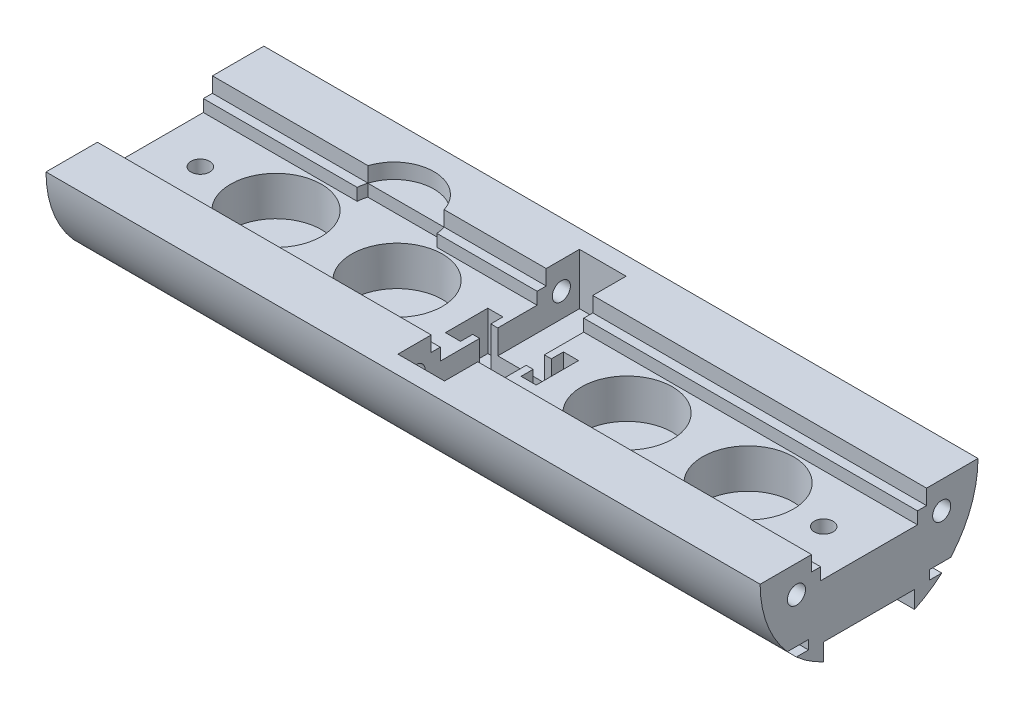
SolidWorks part; units mm, degrees
ref_plane "Front Plane" through (0, 0, 0) normal (0, 0, 1) x (1, 0, 0)
ref_plane "Top Plane" through (0, 0, 0) normal (0, 1, 0) x (1, 0, 0)
ref_plane "Right Plane" through (0, 0, 0) normal (1, 0, 0) x (0, 0, -1)
sketch "Sketch1" plane through (0, 0, 0) normal (1, 0, 0) x (0, 0, -1)
  line L0 (-49.53, 0) -> (-24.13, 0)
  line L1 (-24.13, 0) -> (-24.13, -6.35)
  line L2 (-24.13, -6.35) -> (-20.32, -6.35)
  line L3 (-20.32, -6.35) -> (-20.32, -11.43)
  line L4 (24.13, 0) -> (49.53, 0)
  line L5 (-20.32, -11.43) -> (20.32, -11.43)
  line L6 (20.32, -11.43) -> (20.32, -6.35)
  line L7 (20.32, -6.35) -> (24.13, -6.35)
  line L8 (24.13, -6.35) -> (24.13, 0)
  arc A0 (-49.53, 0) -> (49.53, 0) centre (0, 0) ccw
  dimension "D1" = 99.06
  dimension "D2" = 25.4
  dimension "D3" = 25.4
  dimension "D4" = 6.35
  dimension "D5" = 3.81
  dimension "D6" = 3.81
  dimension "D7" = 5.08
sketch "Sketch3" plane through (0, 0, 0) normal (1, 0, 0) x (0, 0, -1)
  line L0 (-49.53, 0) -> (-24.13, 0)
  line L1 (-24.13, 0) -> (-24.13, -6.35)
  line L2 (-24.13, -6.35) -> (-20.32, -6.35)
  line L3 (-20.32, -6.35) -> (-20.32, -11.43)
  line L4 (-20.32, -11.43) -> (20.32, -11.43)
  line L5 (20.32, -11.43) -> (20.32, -6.35)
  line L6 (20.32, -6.35) -> (24.13, -6.35)
  line L7 (24.13, -6.35) -> (24.13, 0)
  line L8 (24.13, 0) -> (49.53, 0)
  line L9 (0, 0) -> (0, -49.53) construction
  line L10 (19.05, -34.29) -> (-19.05, -34.29)
  line L11 (-19.05, -34.29) -> (-19.05, -45.72)
  line L12 (19.05, -34.29) -> (19.05, -45.72)
  arc A0 (-49.53, 0) -> (-19.05, -45.72) centre (0, 0) ccw
  arc A1 (-49.53, 0) -> (49.53, 0) centre (0, 0) ccw construction
  arc A2 (19.05, -45.72) -> (49.53, 0) centre (0, 0) ccw
  point P28 (0, -34.29)
  dimension "D1" = 15.24
  dimension "D2" = 38.1
extrude "Sled" add sketch "Sketch3" along normal blind 299.72
sketch "Sketch4" plane through (0, 0, 0) normal (1, 0, 0) x (0, 0, -1)
  line L1 (-49.53, 0) -> (-24.13, 0) construction
  line L3 (0, 0) -> (0, -56.3128) construction
  circle A1 centre (-30.48, -11.43) radius 3.81
  circle A2 centre (30.48, -11.43) radius 3.81
  dimension "D1" = 11.43
  dimension "D2" = 19.05
  dimension "D3" = 7.62
sketch "Sketch12" plane through (0, 0, 0) normal (0, 1, 0) x (1, 0, 0)
  line L0 (0, 0) -> (299.72, 0) construction
  line L1 (299.72, 20.32) -> (299.72, -20.32) construction
  line L2 (149.86, 0) -> (149.86, 56.4245) construction
  line L3 (0, -49.53) -> (0, 49.53) construction
  circle A0 centre (50.8, 0) radius 19.05
  circle A3 centre (248.92, 0) radius 19.05
  circle A4 centre (101.6, 0) radius 19.05
  circle A7 centre (198.12, 0) radius 19.05
  dimension "D1" = 38.1
  dimension "D3" = 50.8
  dimension "D4" = 2
extrude "Spring Inserts" cut sketch "Sketch12" against normal blind 27.94
sketch "Sketch13" plane through (0, 0, 0) normal (0, 1, 0) x (1, 0, 0)
  line L0 (0, 0) -> (299.72, 0) construction
  line L1 (299.72, 20.32) -> (299.72, -20.32) construction
  line L2 (149.86, 0) -> (149.86, -49.53) construction
  line L3 (299.72, -49.53) -> (0, -49.53) construction
  line L5 (140.081, 38.1) -> (159.639, 38.1)
  line L6 (140.081, 38.1) -> (140.081, -38.1)
  line L7 (140.081, -38.1) -> (159.639, -38.1)
  line L8 (159.639, 38.1) -> (159.639, -38.1)
  line L9 (140.081, 38.1) -> (159.639, -38.1) construction
  line L10 (140.081, -38.1) -> (159.639, 38.1) construction
  line L11 (299.72, 49.53) -> (0, 49.53) construction
  dimension "D1" = 19.558
  dimension "D2" = 11.43
extrude "Threaded Rod Slots" cut sketch "Sketch4" along normal blind 304.8
extrude "Spring Plate Slot" cut sketch "Sketch13" against normal blind 21.59
ref_plane "Plane1" through (140.081, 0, 0) normal (1, 0, 0) x (0, 0, -1)
sketch "Sketch16" plane through (0, 0, 0) normal (1, 0, 0) x (0, 0, -1)
  line L0 (-45.3974, 5.4215) -> (-55.9821, 1.6857)
  line L1 (-55.9821, 1.6857) -> (-46.4351, -53.4516)
  line L2 (-46.4351, -53.4516) -> (-2.6435, -59.4012)
  line L3 (-2.6435, -59.4012) -> (46.06, -46.1184)
  line L4 (46.06, -46.1184) -> (57.3365, 3.1385)
  line L5 (57.3365, 3.1385) -> (45.3129, 6.0878)
  arc A0 (-45.3974, 5.4215) -> (45.3129, 6.0878) centre (0, 0) ccw
  dimension "D1" = 45.72
extrude "Mod to fit in coupler" cut sketch "Sketch16" against normal blind 77.47 and the other way blind 320.04
sketch "Sketch17" plane through (0, 0, 0) normal (0, 1, 0) x (1, 0, 0)
  line L0 (0, 0) -> (299.72, 0) construction
  line L1 (299.72, 20.32) -> (299.72, -20.32) construction
  line L2 (149.86, 0) -> (149.86, 45.72) construction
  line L3 (0, 45.72) -> (299.72, 45.72) construction
  circle A0 centre (280.67, 0) radius 3.937
  circle A1 centre (248.92, 0) radius 19.05 construction
  circle A2 centre (19.05, 0) radius 3.937
  dimension "D1" = 7.874
  dimension "D2" = 31.75
extrude "Can Cord Holes" cut sketch "Sketch17" against normal blind 62.992
sketch "Sketch18" plane through (0, 0, 0) normal (1, 0, 0) x (0, 0, -1)
  line L0 (0, 0) -> (0, -34.29) construction
  line L1 (-19.05, -34.29) -> (19.05, -34.29) construction
  line L2 (-34.29, -30.2409) -> (-25.4, -30.2409)
  line L3 (-25.4, -30.2409) -> (-25.4, -34.0509)
  line L4 (-25.4, -34.0509) -> (-30.5099, -34.0509)
  line L5 (-30.5099, -34.0509) -> (-38.7668, -32.6466)
  line L6 (-38.7668, -32.6466) -> (-34.29, -30.2409)
  line L7 (25.4, -34.0509) -> (30.5099, -34.0509)
  line L8 (25.4, -30.2409) -> (25.4, -34.0509)
  line L9 (34.29, -30.2409) -> (25.4, -30.2409)
  line L10 (30.5099, -34.0509) -> (38.7668, -32.6466)
  line L11 (38.7668, -32.6466) -> (34.29, -30.2409)
  arc A0 (-45.72, 0) -> (-19.05, -41.5622) centre (0, 0) ccw construction
  dimension "D1" = 8.89
  dimension "D2" = 3.81
  dimension "D3" = 25.4
extrude "Insertion Guide Rails" cut sketch "Sketch18" along normal blind 314.452
sketch "Sketch19" plane through (0, 0, 0) normal (0, 1, 0) x (1, 0, 0)
  line L0 (149.86, 45.72) -> (149.86, -45.72) construction
  line L1 (0, 45.72) -> (299.72, 45.72) construction
  line L2 (299.72, -45.72) -> (0, -45.72) construction
  line L3 (149.86, 0) -> (120.65, 0) construction
  line L4 (162.56, 3.81) -> (137.16, 3.81)
  line L5 (137.16, 3.81) -> (137.16, 8.89)
  line L6 (137.16, 8.89) -> (130.81, 8.89)
  line L7 (130.81, 8.89) -> (130.81, -8.89)
  line L8 (168.91, 8.89) -> (168.91, -8.89)
  line L9 (162.56, 8.89) -> (168.91, 8.89)
  line L10 (162.56, 3.81) -> (162.56, 8.89)
  line L11 (162.56, -8.89) -> (168.91, -8.89)
  line L12 (162.56, -3.81) -> (162.56, -8.89)
  line L13 (162.56, -3.81) -> (137.16, -3.81)
  line L14 (137.16, -3.81) -> (137.16, -8.89)
  line L15 (137.16, -8.89) -> (130.81, -8.89)
  circle A0 centre (101.6, 0) radius 19.05 construction
  point P20 (149.86, 3.81)
  point P21 (168.91, 0)
  point P26 (130.81, 0)
  dimension "D1" = 12.7
  dimension "D2" = 5.08
  dimension "D3" = 6.35
  dimension "D4" = 3.81
extrude "Locking Pin" cut sketch "Sketch19" against normal blind 27.94
sketch "Sketch20" plane through (0, 0, 0) normal (0, 1, 0) x (1, 0, 0)
  line L0 (0, 20.32) -> (0, -20.32) construction
  line L1 (0, 45.72) -> (299.72, 45.72) construction
  circle A0 centre (81.28, 19.05) radius 16.764
  dimension "D1" = 33.528
  dimension "D2" = 81.28
  dimension "D3" = 26.67
extrude "Cut-Extrude1" cut sketch "Sketch20" against normal blind 6.35
sketch "Sketch21" plane through (0, 0, 0) normal (0, 1, 0) x (1, 0, 0)
  line L0 (97.2665, 24.0962) -> (65.2845, 24.0675)
  arc A0 (65.2845, 24.0675) -> (97.2665, 24.0962) centre (81.28, 19.05) ccw
  circle A1 centre (81.28, 19.05) radius 16.764 construction
extrude "Cut-Extrude2" cut sketch "Sketch21" against normal blind 11.43
equation "\"0..75in\"=0.8"
